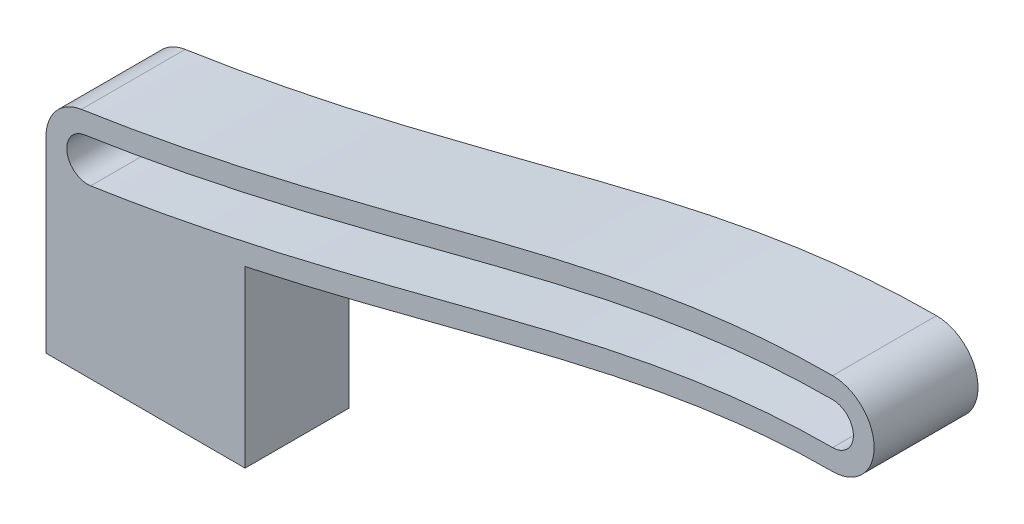
SolidWorks part; units mm, degrees
ref_plane "Front Plane" through (0, 0, 0) normal (0, 0, 1) x (1, 0, 0)
ref_plane "Top Plane" through (0, 0, 0) normal (0, 1, 0) x (1, 0, 0)
ref_plane "Right Plane" through (0, 0, 0) normal (1, 0, 0) x (0, 0, -1)
sketch "Sketch1" plane through (0, 0, 0) normal (0, 0, 1) x (1, 0, 0)
  line L0 (28.2843, 16) -> (0, 0) construction
  line L1 (0, 0) -> (30, 0) construction
  line L2 (0, 0) -> (-7.5855, 9.04) construction
  arc A0 (28.2843, 17) -> (28.2843, 15) centre (28.2843, 16) cw
  arc A1 (-7.7345, 10.0289) -> (-7.4365, 8.0512) centre (-7.5855, 9.04) ccw
  arc A2 (28.2843, 18) -> (28.2843, 14) centre (28.2843, 16) cw
  arc A3 (-7.8836, 11.0177) -> (-7.2874, 7.0624) centre (-7.5855, 9.04) ccw
  spline S0 degree 4 poles (28.2843, 16) (27.9926, 16) (27.4303, 15.9939) (26.5944, 15.9682) (25.4664, 15.9025) (24.2213, 15.7979) (22.8398, 15.6431) (21.3272, 15.4298) (19.705, 15.1551) (17.7486, 14.776) (15.4005, 14.2592) (12.6653, 13.5919) (9.5411, 12.7854) (6.3559, 11.9603) (3.163, 11.1653) (-0.0435, 10.426) (-3.2664, 9.7617) (-6.5945, 9.1714) (-9.94, 8.688) (-12.7892, 8.3773) (-15.031, 8.2006) (-16.4681, 8.1171) (-17.187, 8.0824) (-17.7007, 8.061) (-18.1117, 8.0459) (-18.5228, 8.0328) (-18.934, 8.0219) (-19.2938, 8.0142) (-19.6022, 8.009) (-19.8593, 8.0055) (-20.0648, 8.0033) (-20.2707, 8.0016) (-20.4373, 8.0007) (-20.5666, 8.0003) (-20.6489, 8.0001) (-20.6907, 8.0001) (-20.7128, 8) (-20.7346, 8) (-20.7698, 8) (-20.8088, 8) (-20.7752, 8) (-20.7784, 8) (-20.7931, 8) (-20.8135, 8) (-20.8403, 8) (-20.8605, 8) (-20.8875, 8.0001) (-20.9323, 8.0001) (-20.9939, 8.0003) (-21.0783, 8.0006) (-21.2598, 8.0014) (-21.4837, 8.0031) (-21.7352, 8.0058) (-22.0708, 8.0109) (-22.4079, 8.0175) (-22.8026, 8.0272) (-23.2548, 8.0413) (-23.7086, 8.0585) (-24.0488, 8.0737) (-24.2756, 8.0849) (-24.3889, 8.0908) knots 0 0 0 0 0 0.021821 0.042067 0.062556 0.084519 0.115282 0.146051 0.176819 0.207588 0.264356 0.325894 0.387432 0.448969 0.510507 0.572045 0.633582 0.69512 0.763332 0.82487 0.847947 0.863331 0.871023 0.878715 0.886408 0.8941 0.901792 0.909484 0.91333 0.917176 0.921023 0.924869 0.928715 0.929676 0.930638 0.931119 0.931599 0.93184 0.93208 0.932561 0.932822 0.932953 0.933084 0.933345 0.933607 0.93413 0.934653 0.935699 0.936744 0.938836 0.940928 0.949295 0.953478 0.957662 0.966029 0.974522 0.983014 0.991507 1 1 1 1 1 construction
  spline S1 degree 4 poles (28.2843, 16) (27.9926, 16) (27.4303, 15.9939) (26.5944, 15.9682) (25.4664, 15.9025) (24.2213, 15.7979) (22.8398, 15.6431) (21.3272, 15.4298) (19.705, 15.1551) (17.7486, 14.776) (15.4005, 14.2592) (12.6653, 13.5919) (9.5411, 12.7854) (6.3559, 11.9603) (3.163, 11.1653) (-0.0435, 10.426) (-3.1301, 9.7898) (-5.4225, 9.3795) (-6.9097, 9.1419) (-7.5855, 9.04) knots 0 0 0 0 0 0.021821 0.042067 0.062556 0.084519 0.115282 0.146051 0.176819 0.207588 0.264356 0.325894 0.387432 0.448969 0.510507 0.572045 0.633582 0.684708 0.684708 0.684708 0.684708 0.684708
  spline S2 degree 1 poles (28.2843, 17) (-7.7345, 10.0289) knots 0 0 1 1 construction
  spline S3 degree 3 poles (28.2843, 17) (26.7233, 17) (23.5927, 16.8032) (17.4614, 15.8398) (10.0135, 13.9498) (1.1915, 11.6485) (-4.7432, 10.4798) (-7.7345, 10.0289) knots 0 0 0 0 0.085589 0.171177 0.342354 0.513531 0.684708 0.684708 0.684708 0.684708
  spline S4 degree 1 poles (28.2843, 15) (-7.4365, 8.0512) knots 0 0 1 1 construction
  spline S5 degree 3 poles (28.2843, 15) (25.3, 15) (19.368, 14.2561) (10.5413, 12.0218) (1.6553, 9.7013) (-4.3957, 8.5096) (-7.4365, 8.0512) knots 0 0 0 0 0.171177 0.342354 0.513531 0.684708 0.684708 0.684708 0.684708
  spline S6 degree 1 poles (28.2843, 18) (-7.8836, 11.0177) knots 0 0 1 1 construction
  spline S7 degree 3 poles (28.2843, 18) (26.6869, 18) (23.4762, 17.7981) (17.2462, 16.8177) (9.7488, 14.9139) (0.9598, 12.6221) (-4.917, 11.4649) (-7.8836, 11.0177) knots 0 0 0 0 0.085589 0.171177 0.342354 0.513531 0.684708 0.684708 0.684708 0.684708
  spline S8 degree 1 poles (28.2843, 14) (-7.2874, 7.0624) knots 0 0 1 1 construction
  spline S9 degree 3 poles (28.2843, 14) (26.8322, 14) (23.9423, 13.8184) (18.1071, 12.9063) (10.8077, 11.0576) (1.8865, 8.7278) (-4.2219, 7.5245) (-7.2874, 7.0624) knots 0 0 0 0 0.085589 0.171177 0.342354 0.513531 0.684708 0.684708 0.684708 0.684708
  point P0 (0, 0)
  dimension "D1" = 30
  dimension "D2" = 29.496
  dimension "D3" = 130
  dimension "D4" = 32.4962
  dimension "D5" = 11.8009
  dimension "D6" = 1
  dimension "D8" = 2
extrude "Boss-Extrude1" add sketch "Sketch1" along normal blind 5 contours S9 A2 S7 A3 A0 S5 A1 S3
sketch "Sketch2" plane through (0, 0, 0) normal (0, 0, 1) x (1, 0, 0)
  line L0 (0, 0) -> (0, 8.4055)
  line L1 (0, 0) -> (-9.5855, 0)
  line L2 (-9.5855, 0) -> (-9.5855, 9.04)
  arc A0 (-7.8836, 11.0177) -> (-7.2874, 7.0624) centre (-7.5855, 9.04) ccw construction
  arc A1 (-9.5855, 9.04) -> (-7.2874, 7.0624) centre (-7.5855, 9.04) ccw
  spline S0 degree 3 poles (557.8213, -834.2813) (107.4188, -42.495) (67.7793, 20.6704) (18.1071, 12.9063) (10.8077, 11.0576) (-70.9683, -10.2986) (-178.0357, 30.5499) (173.3161, 990.6183) knots -2.57191 -2.57191 -2.57191 -2.57191 0.085589 0.171177 0.342354 0.513531 4.878465 4.878465 4.878465 4.878465 only from (28.2843, 14) to (-7.2874, 7.0624) construction
  spline S1 degree 3 poles (28.2843, 14) (26.8322, 14) (23.9423, 13.8184) (18.1071, 12.9063) (10.8077, 11.0576) (1.8865, 8.7278) (-4.2219, 7.5245) (-7.2874, 7.0624) knots 0 0 0 0 0.085589 0.171177 0.342354 0.513531 0.684708 0.684708 0.684708 0.684708
  point P5 (-12.0855, 0)
  point P11 (-12.0855, 9.04)
extrude "Boss-Extrude2" add sketch "Sketch2" along normal up to surface (5 mm away) contours L0 S1 A1 L2 L1 up to face at (19.3224, 14.1855, 5)
